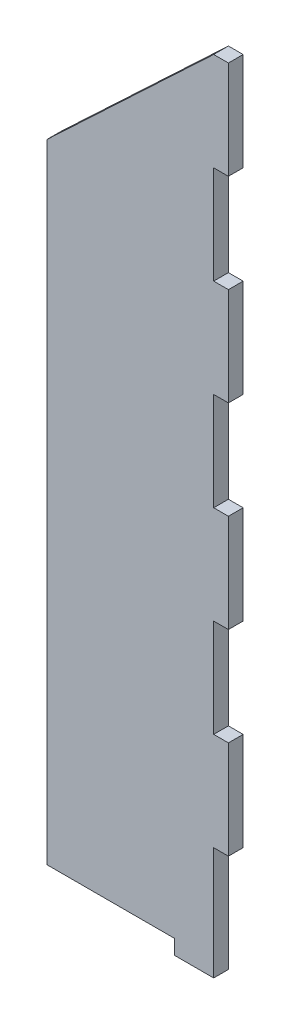
SolidWorks part; units mm, degrees
ref_plane "Front Plane" through (0, 0, 0) normal (0, 0, 1) x (1, 0, 0)
ref_plane "Top Plane" through (0, 0, 0) normal (0, 1, 0) x (1, 0, 0)
ref_plane "Right Plane" through (0, 0, 0) normal (1, 0, 0) x (0, 0, -1)
sketch "Sketch1" plane through (0, 0, 0) normal (0, 0, 1) x (1, 0, 0)
  line L0 (-26.9875, -101.6) -> (-26.9875, 101.6)
  line L1 (-26.9875, 101.6) -> (26.9875, 152.4)
  line L2 (26.9875, 152.4) -> (26.9875, -101.6)
  line L3 (26.9875, -101.6) -> (-26.9875, -101.6)
  line L4 (-26.9875, 0) -> (26.9875, 0) construction
  line L5 (26.9875, 120.65) -> (26.9875, 88.9)
  line L6 (26.9875, 152.4) -> (31.75, 152.4)
  line L7 (26.9875, 152.4) -> (26.9875, 120.65)
  line L8 (26.9875, 120.65) -> (31.75, 120.65)
  line L9 (31.75, 152.4) -> (31.75, 120.65)
  line L10 (26.9875, 120.65) -> (31.75, 120.65)
  line L11 (31.75, 120.65) -> (31.75, 88.9)
  line L12 (26.9875, 88.9) -> (31.75, 88.9)
  line L13 (26.9875, 88.9) -> (26.9875, 57.15)
  line L14 (26.9875, 88.9) -> (31.75, 88.9)
  line L15 (31.75, 88.9) -> (31.75, 57.15)
  line L16 (26.9875, 57.15) -> (31.75, 57.15)
  line L17 (26.9875, 57.15) -> (26.9875, 25.4)
  line L18 (26.9875, 57.15) -> (31.75, 57.15)
  line L19 (31.75, 57.15) -> (31.75, 25.4)
  line L20 (26.9875, 25.4) -> (31.75, 25.4)
  line L21 (26.9875, 25.4) -> (26.9875, -6.35)
  line L22 (26.9875, 25.4) -> (31.75, 25.4)
  line L23 (31.75, 25.4) -> (31.75, -6.35)
  line L24 (26.9875, -6.35) -> (31.75, -6.35)
  line L25 (26.9875, -6.35) -> (26.9875, -38.1)
  line L26 (26.9875, -6.35) -> (31.75, -6.35)
  line L27 (31.75, -6.35) -> (31.75, -38.1)
  line L28 (26.9875, -38.1) -> (31.75, -38.1)
  line L29 (26.9875, -38.1) -> (26.9875, -69.85)
  line L30 (26.9875, -38.1) -> (31.75, -38.1)
  line L31 (31.75, -38.1) -> (31.75, -69.85)
  line L32 (26.9875, -69.85) -> (31.75, -69.85)
  line L33 (26.9875, -69.85) -> (26.9875, -101.6)
  line L42 (26.9875, -69.85) -> (31.75, -69.85)
  line L43 (31.75, -69.85) -> (31.75, -101.6)
  line L44 (26.9875, -101.6) -> (31.75, -101.6)
  line L46 (14.2875, -101.6) -> (26.9875, -101.6)
  line L47 (14.2875, -101.6) -> (14.2875, -106.3625)
  line L48 (14.2875, -106.3625) -> (26.9875, -106.3625)
  line L49 (26.9875, -101.6) -> (26.9875, -106.3625)
  point P2 (0, 0)
  dimension "D1" = 53.975
  dimension "D2" = 254
  dimension "D3" = 203.2
  dimension "D4" = 4.7625
  dimension "D6" = 31.75
  dimension "D7" = 12.7
  dimension "D8" = 4.7625
  dimension "D5" = 8
extrude "Boss-Extrude1" add sketch "Sketch1" along normal blind 4.7625
equation "\"Height\"= 12in"
equation "\"Depth\"= 7in"
equation "\"WallThickness\"= 0.1875in"
equation "\"FloorThickness\"= 0.1875in"
equation "\"D1@Sketch1\"=(\"Depth\"-2.75)/2"
equation "\"D4@Sketch1\"=\"WallThickness\""
equation "\"D6@Sketch1\"=\"D2@Sketch1\"/\"D5@Sketch1\""
equation "\"D8@Sketch1\"=\"FloorThickness\""
equation "\"D1@Boss-Extrude1\"=\"WallThickness\""
equation "\"Width\" = 30in"
